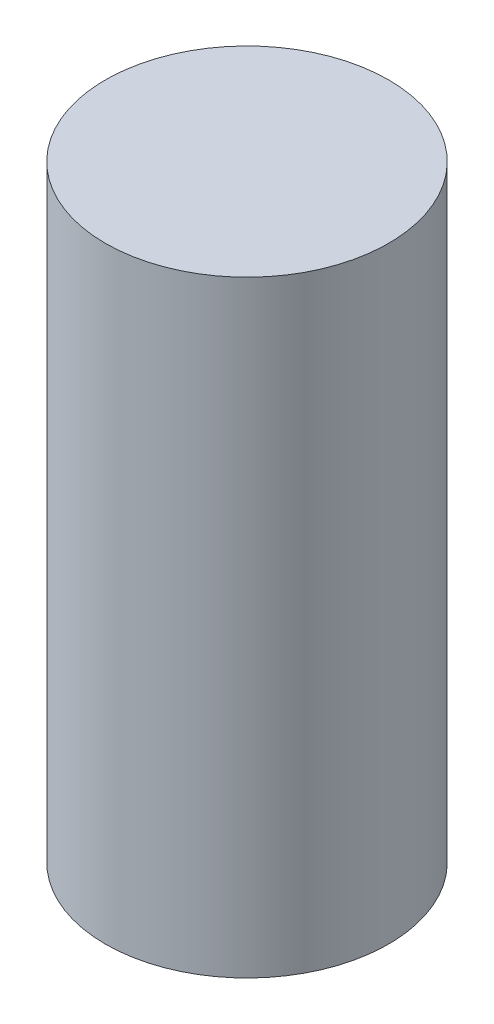
SolidWorks part; units mm, degrees
ref_plane "Front Plane" through (0, 0, 0) normal (0, 0, 1) x (1, 0, 0)
ref_plane "Top Plane" through (0, 0, 0) normal (0, 1, 0) x (1, 0, 0)
ref_plane "Right Plane" through (0, 0, 0) normal (1, 0, 0) x (0, 0, -1)
other "Configuration Table"
sketch "Sketch1" plane through (0, 0, 0) normal (0, 1, 0) x (1, 0, 0)
  circle A0 centre (350, 300) radius 14
extrude "OVEN_kesme_gobek_D28" add sketch "Sketch1" along normal blind 60 from offset 400 separate body
